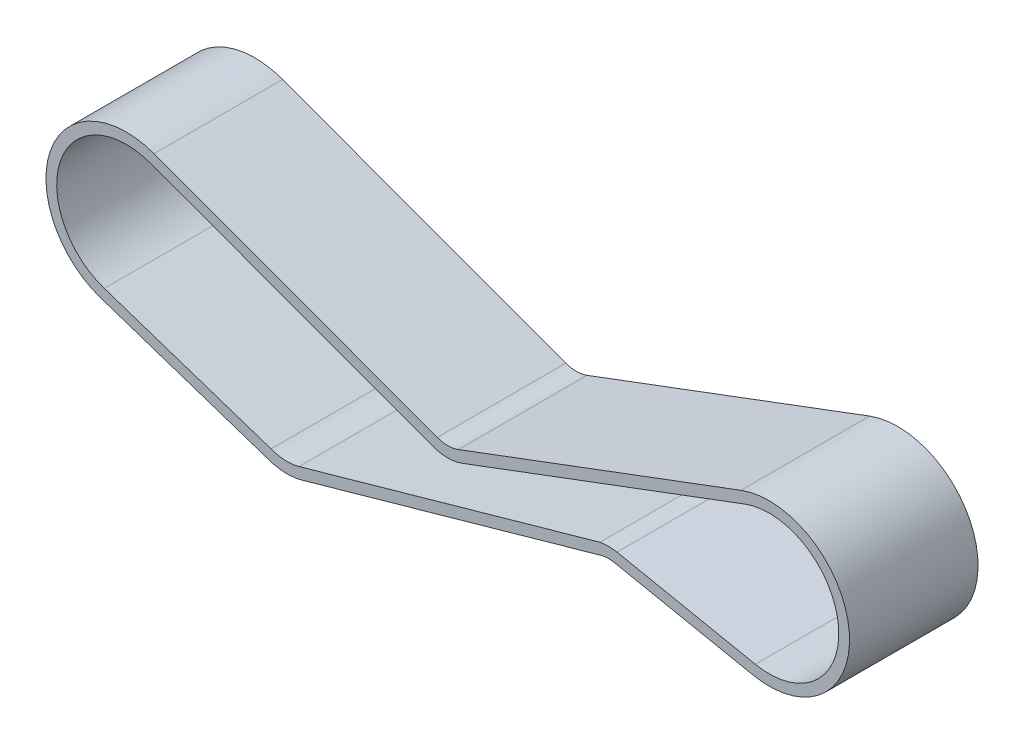
SolidWorks part; units mm, degrees
ref_plane "Front Plane" through (0, 0, 0) normal (0, 0, 1) x (1, 0, 0)
ref_plane "Top Plane" through (0, 0, 0) normal (0, 1, 0) x (1, 0, 0)
ref_plane "Right Plane" through (0, 0, 0) normal (1, 0, 0) x (0, 0, -1)
sketch "Sketch1" plane through (0, 0, 0) normal (0, 0, 1) x (1, 0, 0)
  line L0 (-28.2807, 6.0943) -> (-1.8496, -3.6181)
  line L1 (0.8284, -3.6092) -> (27.1945, 6.2792)
  line L2 (15.275, -3.565) -> (28.188, -6.1778)
  line L3 (13.6798, -3.565) -> (-14.4003, -11.4857)
  line L4 (-17.0127, -11.3631) -> (-32.5786, -6.1732)
  line L5 (0.4772, -2.6729) -> (26.8434, 7.2155)
  line L6 (-27.9358, 7.0329) -> (-1.5047, -2.6795)
  line L7 (-17.35, -12.3048) -> (-32.8949, -7.1218)
  line L8 (13.9124, -4.5384) -> (-14.1288, -12.4482)
  line L9 (15.0766, -4.5451) -> (27.9896, -7.1579)
  arc A0 (-28.2807, 6.0943) -> (-32.5786, -6.1732) centre (-30.5226, -0.0069) ccw
  arc A1 (28.188, -6.1778) -> (27.1945, 6.2792) centre (29.477, 0.1931) ccw
  arc A2 (-17.0127, -11.3631) -> (-14.4003, -11.4857) centre (-15.5226, -7.5069) ccw
  arc A3 (-1.8496, -3.6181) -> (0.8284, -3.6092) centre (-0.5226, -0.0069) ccw
  arc A4 (15.275, -3.565) -> (13.6798, -3.565) centre (14.4774, -7.5069) ccw
  arc A5 (27.9896, -7.1579) -> (26.8434, 7.2155) centre (29.477, 0.1931) ccw
  arc A6 (-1.5047, -2.6795) -> (0.4772, -2.6729) centre (-0.5226, -0.0069) ccw
  arc A7 (-27.9358, 7.0329) -> (-32.8949, -7.1218) centre (-30.5226, -0.0069) ccw
  arc A8 (-17.35, -12.3048) -> (-14.1288, -12.4482) centre (-15.5226, -7.5069) ccw
  arc A9 (15.0766, -4.5451) -> (13.9124, -4.5384) centre (14.4774, -7.5069) ccw
extrude "Boss-Extrude1" add sketch "Sketch1" along normal blind 12
